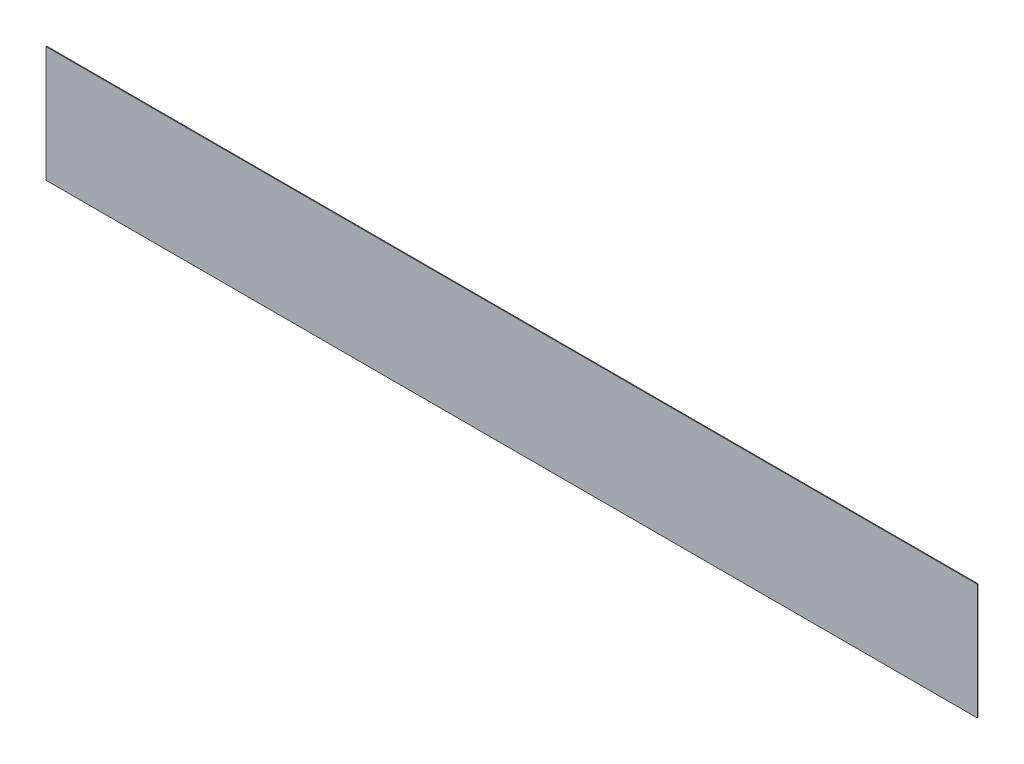
SolidWorks part; units mm, degrees
ref_plane "Front Plane" through (0, 0, 0) normal (0, 0, 1) x (1, 0, 0)
ref_plane "Top Plane" through (0, 0, 0) normal (0, 1, 0) x (1, 0, 0)
ref_plane "Right Plane" through (0, 0, 0) normal (1, 0, 0) x (0, 0, -1)
sketch "Sketch1" plane through (0, 0, 0) normal (0, 0, 1) x (1, 0, 0)
  line L0 (2500, 311) -> (2500, 0)
  line L1 (2500, 311) -> (0, 311)
  line L2 (2500, 0) -> (0, 0)
  line L3 (0, 311) -> (0, 0)
other "Pen Sketch1" parameters "D1"=69.7562, "D2"=44.2015
extrude "Boss-Extrude1" add sketch "Sketch1" along normal blind 2
